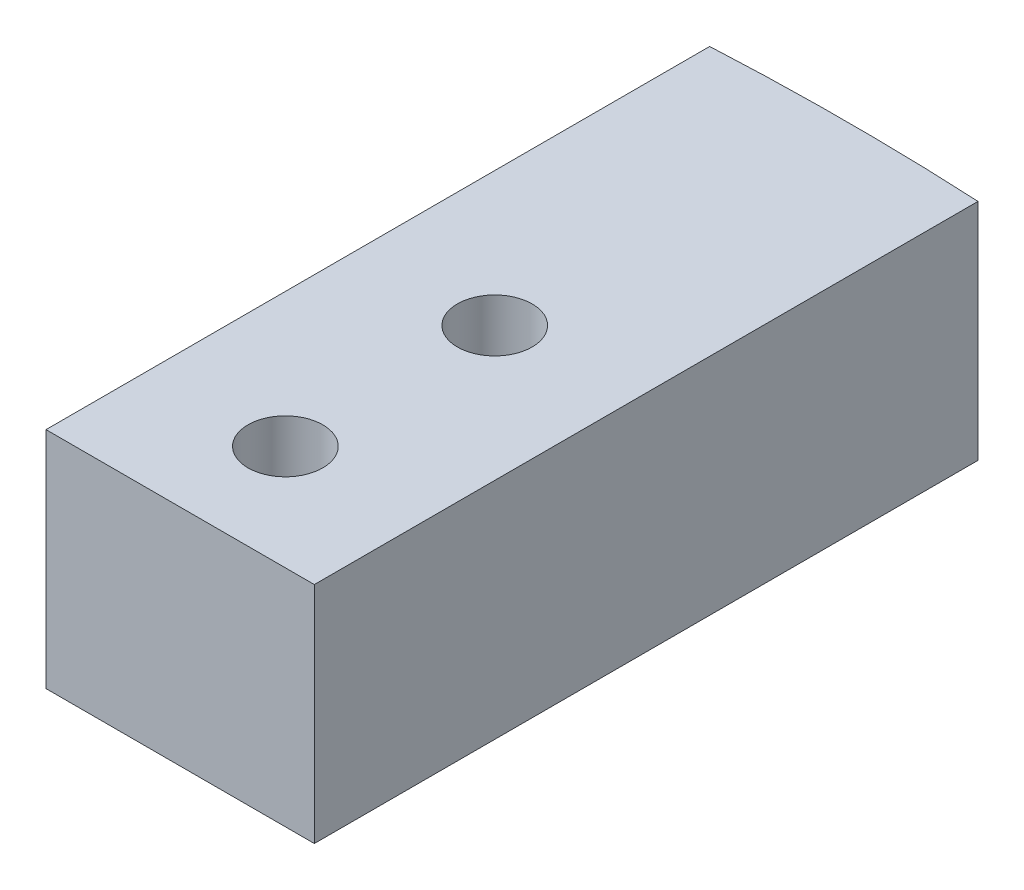
SolidWorks part; units mm, degrees
ref_plane "Front Plane" through (0, 0, 0) normal (0, 0, 1) x (1, 0, 0)
ref_plane "Top Plane" through (0, 0, 0) normal (0, 1, 0) x (1, 0, 0)
ref_plane "Right Plane" through (0, 0, 0) normal (1, 0, 0) x (0, 0, -1)
sketch "Sketch1" plane through (0, 0, 0) normal (0, 1, 0) x (1, 0, 0)
  line L0 (-7.5, -0.1934) -> (-8.9727, 28.3436)
  line L1 (7.5, -0.1934) -> (8.9727, 28.3436)
  line L2 (-7.5, -0.1934) -> (-7.0268, -9.3639)
  line L3 (7.0268, -9.3639) -> (7.5, -0.1934)
  arc A0 (-8.9727, 28.3436) -> (8.9727, 28.3436) centre (0, -145.5262) cw
  arc A1 (-7.5, -0.1934) -> (7.5, -0.1934) centre (0, -145.5262) cw construction
  arc A2 (-7.0268, -9.3639) -> (7.0268, -9.3639) centre (0, -9.0012) ccw
  point P10 (0, 0)
  point P11 (0, -8.7469)
  dimension "D1" = 28.575
  dimension "D2" = 145.5262
  dimension "D3" = 15
  dimension "D4" = 136.525
extrude "Boss-Extrude1" add sketch "Sketch1" along normal mid plane 15
hole_wizard "M6x1.0 Tapped Hole1" positions "Sketch4" profile "Sketch5" tap size "M6x1.0" standard "ANSI Metric" end condition through all
sketch "Sketch4" plane through (0, 7.5, 0) normal (0, 1, 0) x (1, 0, 0)
  point P0 (0, -9.0012)
  point P3 (0, 5)
  dimension "D1" = 5
sketch "Sketch5" plane through (0, 7.5, 9.0012) normal (1, 0, 0) x (0, 0, 1)
  line L0 (0, 0) -> (0, 15)
  line L1 (0, 15) -> (2.5, 15)
  line L2 (2.5, 15) -> (2.5, 0)
  line L5 (2.5, 0) -> (0, 0)
  line L11 (0, -6.35) -> (0, 107.95) construction
  dimension "Thru Tap Drill Dia." = 5
  dimension "Thru Tap Drill Depth" = 15
cosmetic thread "Hole Thread2" parameters "D2"=6
cosmetic thread "Hole Thread3" parameters "D2"=6
sketch "Sketch6" plane through (0, 7.5, 0) normal (0, 1, 0) x (1, 0, 0)
  line L0 (7.0268, -9.3639) -> (8.9727, 28.3436) construction
  line L1 (-8.9727, 28.3436) -> (8.9727, 28.3436)
  line L2 (-8.9727, 28.3436) -> (-8.9727, -16.0373)
  line L3 (-8.9727, -16.0373) -> (8.9727, -16.0373)
  line L4 (8.9727, 28.3436) -> (8.9727, -16.0373)
  arc A0 (-7.0268, -9.3639) -> (7.0268, -9.3639) centre (0, -9.0012) ccw construction
  circle A1 centre (0, -9.0012) radius 2.5 construction
  circle A2 centre (0, 5) radius 2.5 construction
  circle A3 centre (0, -9.0012) radius 2.5
  circle A4 centre (0, 5) radius 2.5
  point P8 (8.9727, 28.3436)
extrude "Boss-Extrude2" add sketch "Sketch6" against normal through all
sketch "Sketch8" plane through (0, 0, 0) normal (0, 0, 1) x (1, 0, 0)
  circle A0 centre (0, 0) radius 2.5
  dimension "D1" = 5
extrude "Cut-Extrude1" cut sketch "Sketch8" against normal blind 20 from offset 15
